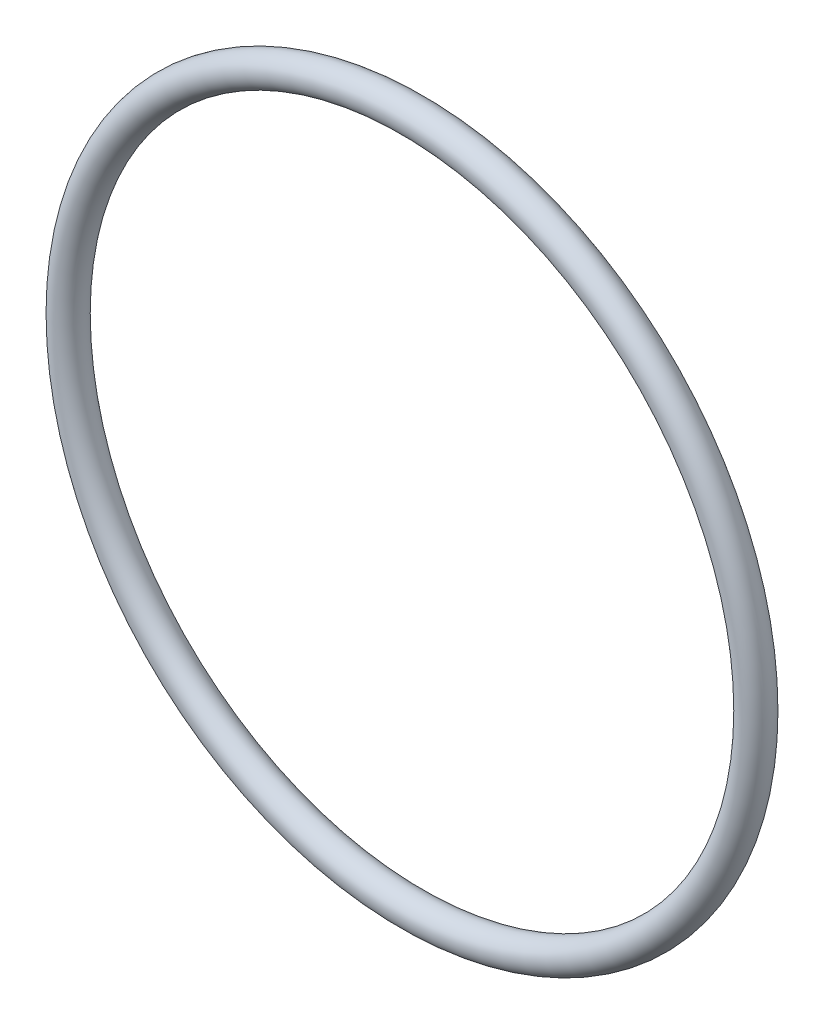
SolidWorks part; units mm, degrees
material "Caoutchouc"
ref_plane "Plan de face" through (0, 0, 0) normal (0, 0, 1) x (1, 0, 0)
ref_plane "Plan de dessus" through (0, 0, 0) normal (0, 1, 0) x (1, 0, 0)
ref_plane "Plan de droite" through (0, 0, 0) normal (1, 0, 0) x (0, 0, -1)
sketch "Esquisse1" plane through (0, 0, 0) normal (1, 0, 0) x (0, 0, -1)
  line L0 (0, 0) -> (0, -22) construction
  line L1 (-13.3923, 0) -> (16.9598, 0) construction
  circle A0 centre (0, -22) radius 1
  point P7 (0, 0)
  point P8 (-13.3923, 0)
  point P9 (0, 0)
  point P10 (0, 0)
  dimension "D1" = 2
  dimension "D2" = 22
revolve "Révolution3" add sketch "Esquisse1" angle 360 about L1
